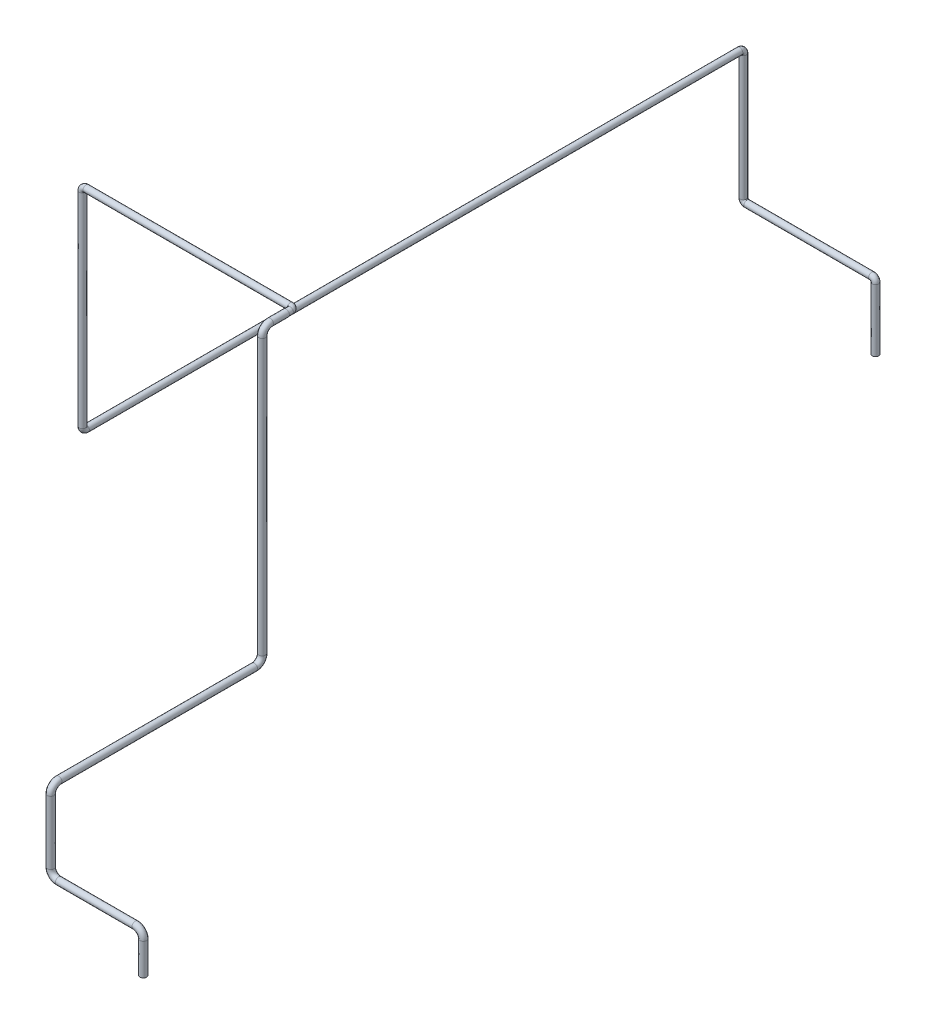
SolidWorks part; units mm, degrees
ref_plane "Alzado" through (0, 0, 0) normal (0, 0, 1) x (1, 0, 0)
ref_plane "Planta" through (0, 0, 0) normal (0, 1, 0) x (1, 0, 0)
ref_plane "Vista lateral" through (0, 0, 0) normal (1, 0, 0) x (0, 0, -1)
sketch "Croquis1" plane through (0, 0, 0) normal (0, 0, 1) x (1, 0, 0)
  circle A0 centre (0, 0) radius 12.7
  dimension "D1" = 25.4
extrude "Saliente-Extruir1" add sketch "Croquis1" along normal blind 20
sketch3d "Croquis3D1"
  line L0 (0, 0, 20) -> (0, 0, 60)
  line L1 (0, 0, 20) -> (0, 0, 0) construction
  line L2 (0, -30, 90) -> (0, -1070, 90)
  line L3 (0, -1100, 120) -> (0, -1100, 860)
  line L4 (0, -1130, 890) -> (0, -1370, 890)
  line L5 (30, -1400, 890) -> (320, -1400, 890)
  line L6 (350, -1430, 890) -> (350, -1550, 890)
  arc A0 (320, -1400, 890) -> (350, -1430, 890) centre (320, -1430, 890) ccw
  arc A1 (0, -1100, 860) -> (0, -1130, 890) centre (0, -1130, 860) ccw
  arc A2 (0, -1070, 90) -> (0, -1100, 120) centre (0, -1070, 120) ccw
  arc A3 (0, 0, 60) -> (0, -30, 90) centre (0, -30, 60) ccw
  arc A4 (0, -1370, 890) -> (30, -1400, 890) centre (30, -1370, 890) ccw
  point P11 (350, -1400, 890)
  point P12 (320, -1430, 860)
  point P15 (0, -1100, 890)
  point P16 (30, -1130, 860)
  point P19 (0, -1100, 90)
  point P20 (-30, -1070, 120)
  point P23 (0, 0, 90)
  point P24 (30, -30, 60)
  point P27 (0, -1400, 890)
  point P28 (30, -1370, 920)
  dimension "D7" = 30
  dimension "D8" = 30
  dimension "D1" = 70
  dimension "D2" = 1100
  dimension "D3" = 800
  dimension "D5" = 350
  dimension "D4" = 300
  dimension "D6" = 150
sketch "Croquis2" plane through (0, 0, 20) normal (0, 0, 1) x (1, 0, 0)
  circle A0 centre (0, 0) radius 12.7
sweep "Barrer1" add profiles "Croquis2" path "Croquis3D1"
sketch3d "Croquis3D2"
  line L0 (0, 0, 0) -> (0, 0, -16)
  line L1 (0, 0, 60) -> (0, 0, 0) construction
  line L2 (-14, 0, -30) -> (-786, 0, -30)
  line L3 (-800, -14, -30) -> (-800, -786, -30)
  line L4 (-800, -800, -44) -> (-800, -800, -2516)
  line L5 (-800, -814, -2530) -> (-800, -1286, -2530)
  line L6 (-786, -1300, -2530) -> (-314, -1300, -2530)
  line L7 (-300, -1314, -2530) -> (-300, -1550, -2530)
  arc A0 (-314, -1300, -2530) -> (-300, -1314, -2530) centre (-314, -1314, -2530) ccw
  arc A1 (-800, -1286, -2530) -> (-786, -1300, -2530) centre (-786, -1286, -2530) ccw
  arc A2 (-800, -800, -2516) -> (-800, -814, -2530) centre (-800, -814, -2516) ccw
  arc A3 (-800, -786, -30) -> (-800, -800, -44) centre (-800, -786, -44) ccw
  arc A4 (-786, 0, -30) -> (-800, -14, -30) centre (-786, -14, -30) ccw
  arc A5 (0, 0, -16) -> (-14, 0, -30) centre (-14, 0, -16) ccw
  point P13 (-300, -1300, -2530)
  point P14 (-314, -1314, -2544)
  point P17 (-800, -1300, -2530)
  point P18 (-786, -1286, -2516)
  point P21 (-800, -800, -2530)
  point P22 (-814, -814, -2516)
  point P25 (-800, -800, -30)
  point P26 (-786, -786, -44)
  point P29 (-800, 0, -30)
  point P30 (-786, -14, -16)
  point P33 (0, 0, -30)
  point P34 (-14, 14, -16)
  dimension "D8" = 14
  dimension "D1" = 30
  dimension "D2" = 800
  dimension "D3" = 800
  dimension "D4" = 2500
  dimension "D5" = 500
  dimension "D6" = 500
  dimension "D7" = 250
sketch "Croquis3" plane through (0, 0, 0) normal (0, 0, -1) x (-1, 0, 0)
  circle A0 centre (0, 0) radius 12
  dimension "D1" = 24
sweep "Barrer2" add profiles "Croquis3" path "Croquis3D2"
